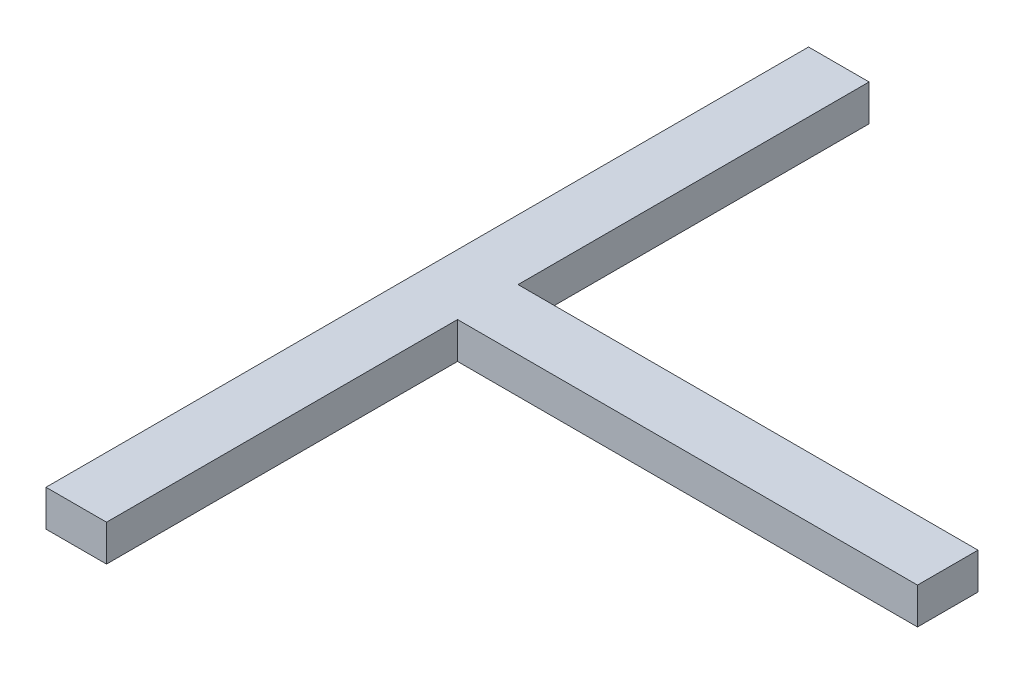
SolidWorks part; units mm, degrees
ref_plane "Front Plane" through (0, 0, 0) normal (0, 0, 1) x (1, 0, 0)
ref_plane "Top Plane" through (0, 0, 0) normal (0, 1, 0) x (1, 0, 0)
ref_plane "Right Plane" through (0, 0, 0) normal (1, 0, 0) x (0, 0, -1)
sketch "Sketch1" plane through (0, 0, 0) normal (0, 1, 0) x (1, 0, 0)
  line L0 (0, 0) -> (71.488, 0) construction
  line L1 (2.5, 31.5) -> (-2.5, 31.5)
  line L2 (2.5, 31.5) -> (2.5, 2.5)
  line L3 (2.5, -31.5) -> (-2.5, -31.5)
  line L4 (-2.5, 31.5) -> (-2.5, -31.5)
  line L5 (2.5, 31.5) -> (-2.5, -31.5) construction
  line L6 (2.5, -31.5) -> (-2.5, 31.5) construction
  line L7 (2.5, -2.5) -> (2.5, -31.5)
  line L8 (2.5, 2.5) -> (40.5, 2.5)
  line L10 (2.5, -2.5) -> (40.5, -2.5)
  line L11 (40.5, 2.5) -> (40.5, -2.5)
  point P0 (0, 0)
  dimension "D1" = 63
  dimension "D2" = 5
  dimension "D3" = 5
  dimension "D4" = 38
  dimension "D5" = 2.5
extrude "Boss-Extrude1" add sketch "Sketch1" along normal blind 3
